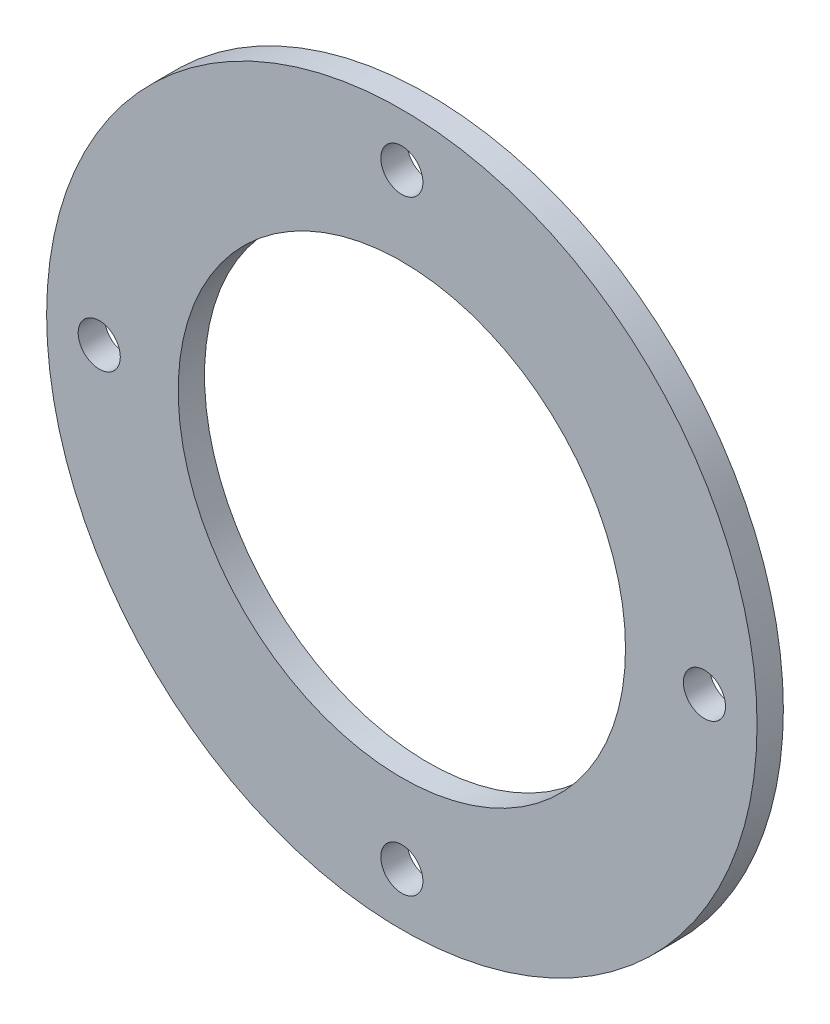
SolidWorks part; units mm, degrees
material "环氧树脂FR-4"
ref_plane "前视基准面" through (0, 0, 0) normal (0, 0, 1) x (1, 0, 0)
ref_plane "上视基准面" through (0, 0, 0) normal (0, 1, 0) x (1, 0, 0)
ref_plane "右视基准面" through (0, 0, 0) normal (1, 0, 0) x (0, 0, -1)
sketch "草图1" plane through (0, 0, 0) normal (0, 0, 1) x (1, 0, 0)
  line L1 (0, 0) -> (0, 23) construction
  circle A0 centre (0, 0) radius 27
  circle A1 centre (0, 0) radius 17
  circle A2 centre (0, 23) radius 1.6
  circle A3 centre (23, 0) radius 1.6
  circle A4 centre (0, -23) radius 1.6
  circle A5 centre (-23, 0) radius 1.6
  dimension "D1" = 34
  dimension "D2" = 54
  dimension "D4" = 3.2
  dimension "D3" = 23
  dimension "D5" = 4
extrude "凸台-拉伸1" add sketch "草图1" along normal blind 2
